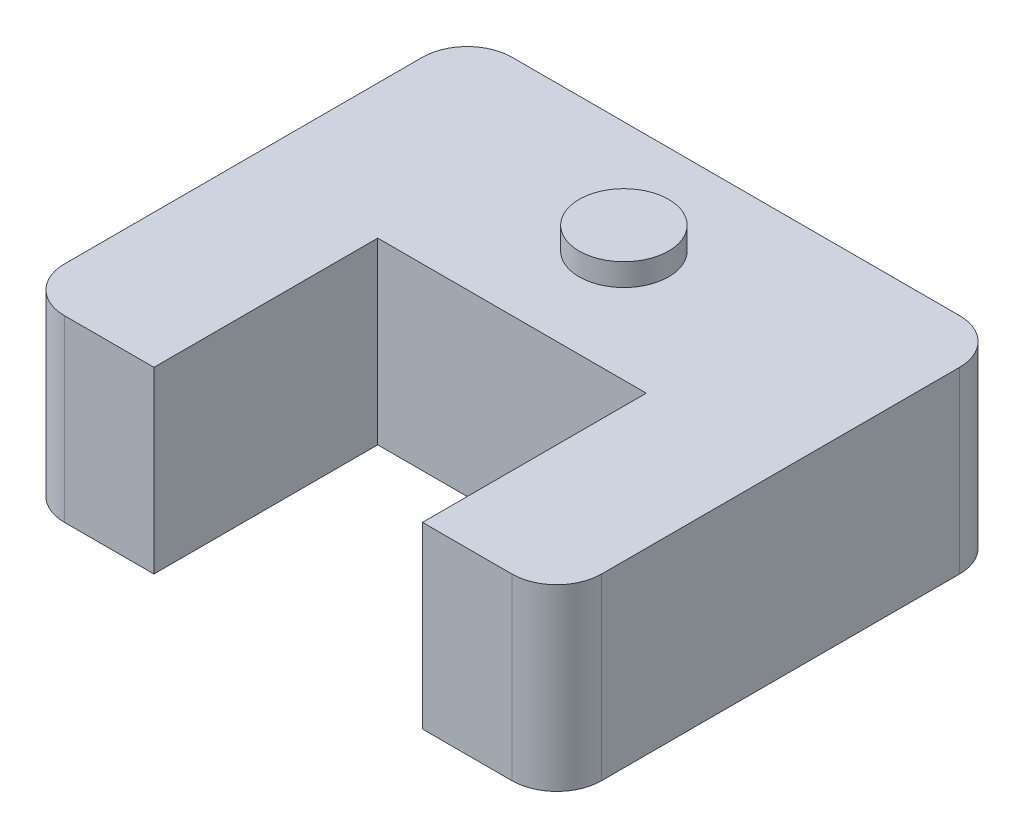
SolidWorks part; units mm, degrees
ref_plane "Front Plane" through (0, 0, 0) normal (0, 0, 1) x (1, 0, 0)
ref_plane "Top Plane" through (0, 0, 0) normal (0, 1, 0) x (1, 0, 0)
ref_plane "Right Plane" through (0, 0, 0) normal (1, 0, 0) x (0, 0, -1)
sketch "Sketch1" plane through (0, 0, 0) normal (0, 0, 1) x (1, 0, 0)
  line L1 (0, 0) -> (-304.8, 0)
  line L2 (0, 0) -> (0, 101.6)
  line L3 (0, 101.6) -> (-304.8, 101.6)
  line L4 (-304.8, 0) -> (-304.8, 101.6)
  line L5 (-152.4, 0) -> (-228.6, 0)
  line L6 (-152.4, 0) -> (-152.4, 101.6)
  line L7 (-152.4, 101.6) -> (-228.6, 101.6)
  line L8 (-228.6, 0) -> (-228.6, 101.6)
  line L9 (-152.4, 101.6) -> (-76.2, 101.6)
  line L10 (-152.4, 101.6) -> (-152.4, 0)
  line L11 (-152.4, 0) -> (-76.2, 0)
  line L12 (-76.2, 101.6) -> (-76.2, 0)
extrude "Boss-Extrude1" add sketch "Sketch1" against normal blind 254 contours L2 L1 L4 L3
sketch "Sketch3" plane through (0, 0, 0) normal (0, 0, 1) x (1, 0, 0)
  line L1 (0, 101.6) -> (-304.8, 101.6) construction
  line L2 (-228.6, 0) -> (-76.2, 0)
  line L3 (-228.6, 0) -> (-228.6, 101.6)
  line L4 (-228.6, 101.6) -> (-76.2, 101.6)
  line L5 (-76.2, 0) -> (-76.2, 101.6)
extrude "Cut-Extrude1" cut sketch "Sketch3" against normal blind 127
fillet "Fillet1" radius 25.4 4 edges at (-304.8, 50.8, -254) (0, 50.8, -254) (0, 50.8, 0) (-304.8, 50.8, 0)
sketch "Sketch4" plane through (0, 101.6, 0) normal (0, 1, 0) x (1, 0, 0)
  circle A0 centre (-152.4, 190.5) radius 25.4
extrude "Boss-Extrude2" add sketch "Sketch4" along normal blind 12.7 contours A0
